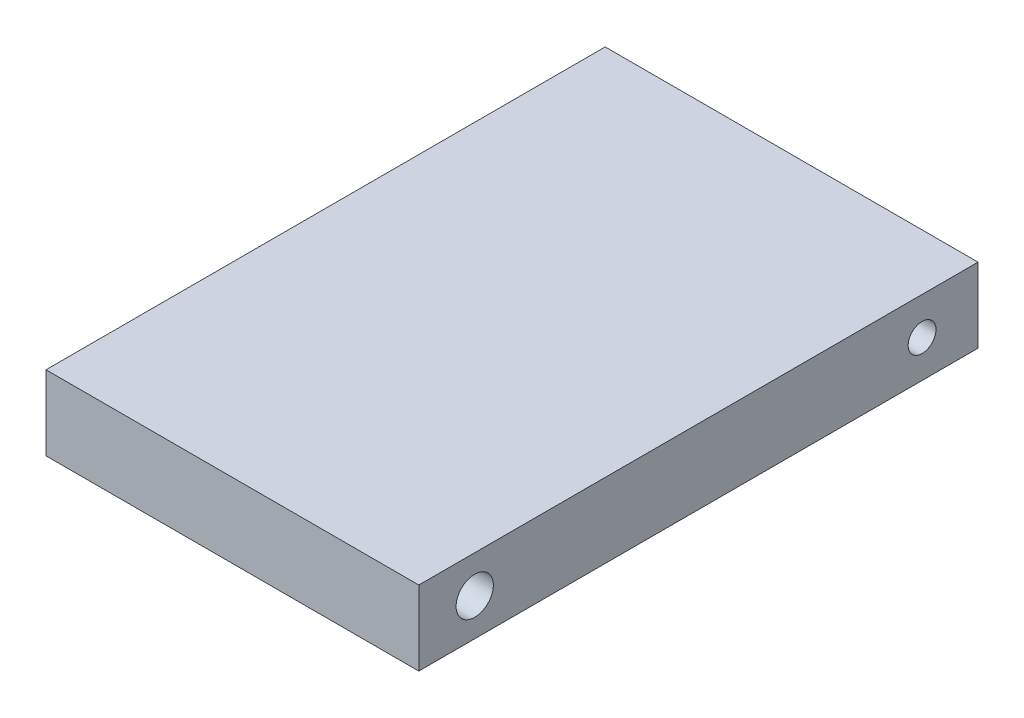
SolidWorks part; units mm, degrees
ref_plane "Front Plane" through (0, 0, 0) normal (0, 0, 1) x (1, 0, 0)
ref_plane "Top Plane" through (0, 0, 0) normal (0, 1, 0) x (1, 0, 0)
ref_plane "Right Plane" through (0, 0, 0) normal (1, 0, 0) x (0, 0, -1)
sketch "Sketch1" plane through (0, 0, 0) normal (0, 1, 0) x (1, 0, 0)
  line L0 (0, 0) -> (127, 0)
  line L1 (127, 0) -> (127, 190.5)
  line L2 (127, 190.5) -> (0, 190.5)
  line L3 (0, 190.5) -> (0, 0)
  dimension "D1" = 127
  dimension "D2" = 190.5
extrude "Boss-Extrude1" add sketch "Sketch1" along normal blind 25.4
sketch "Sketch2" plane through (127, 0, 0) normal (1, 0, 0) x (0, 0, -1)
  line L0 (0, 25.4) -> (0, 0) construction
  line L3 (0, 25.4) -> (190.5, 25.4) construction
  circle A0 centre (19.05, 12.7) radius 6.35
  dimension "D3" = 12.7
  dimension "D1" = 19.05
  dimension "D2" = 12.7
extrude "Cut-Extrude1" cut sketch "Sketch2" against normal blind 19.05 contours A0
sketch "Sketch3" plane through (127, 0, 0) normal (1, 0, 0) x (0, 0, -1)
  line L0 (0, 0) -> (190.5, 0) construction
  line L1 (190.5, 25.4) -> (190.5, 0) construction
  circle A0 centre (171.45, 12.7) radius 4.7411
  dimension "D1" = 12.7
  dimension "D2" = 19.05
extrude "Cut-Extrude2" cut sketch "Sketch3" against normal blind 19.05 contours A0
sketch "Sketch8" plane through (0, 0, 0) normal (-1, 0, 0) x (0, 0, 1)
  line L0 (-190.5, 0) -> (0, 0) construction
  line L1 (-190.5, 25.4) -> (-190.5, 0) construction
  line L2 (0, 25.4) -> (0, 0) construction
  circle A0 centre (-171.45, 12.7) radius 6.35
  circle A1 centre (-19.05, 12.7) radius 6.35
  dimension "D5" = 12.7
  dimension "D6" = 12.7
  dimension "D1" = 12.7
  dimension "D2" = 19.05
  dimension "D3" = 12.7
  dimension "D4" = 19.05
extrude "Cut-Extrude3" cut sketch "Sketch8" against normal blind 19.05
